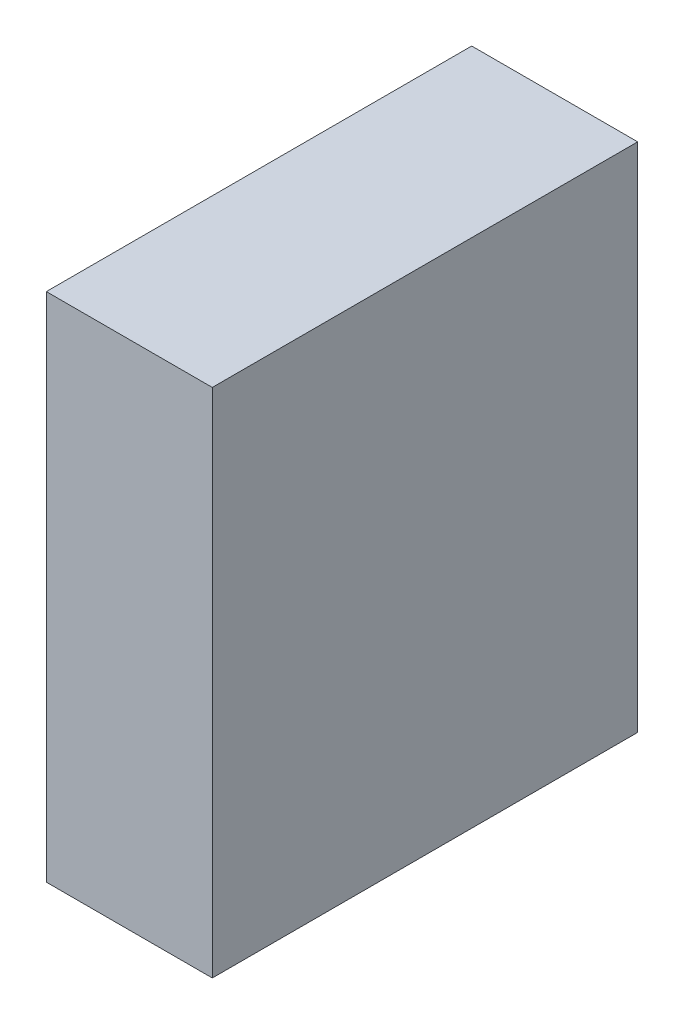
SolidWorks part; units mm, degrees
ref_plane "Front Plane" through (0, 0, 0) normal (0, 0, 1) x (1, 0, 0)
ref_plane "Top Plane" through (0, 0, 0) normal (0, 1, 0) x (1, 0, 0)
ref_plane "Right Plane" through (0, 0, 0) normal (1, 0, 0) x (0, 0, -1)
sketch "Sketch2" plane through (0, 0, 0) normal (0, 0, 1) x (1, 0, 0)
  line L1 (0, 0) -> (12.9, 0)
  line L2 (0, 0) -> (0, -39.75)
  line L3 (0, -39.75) -> (12.9, -39.75)
  line L4 (12.9, 0) -> (12.9, -39.75)
  dimension "D1" = 12.9
  dimension "D2" = 39.75
extrude "Boss-Extrude1" add sketch "Sketch2" along normal blind 33.06
